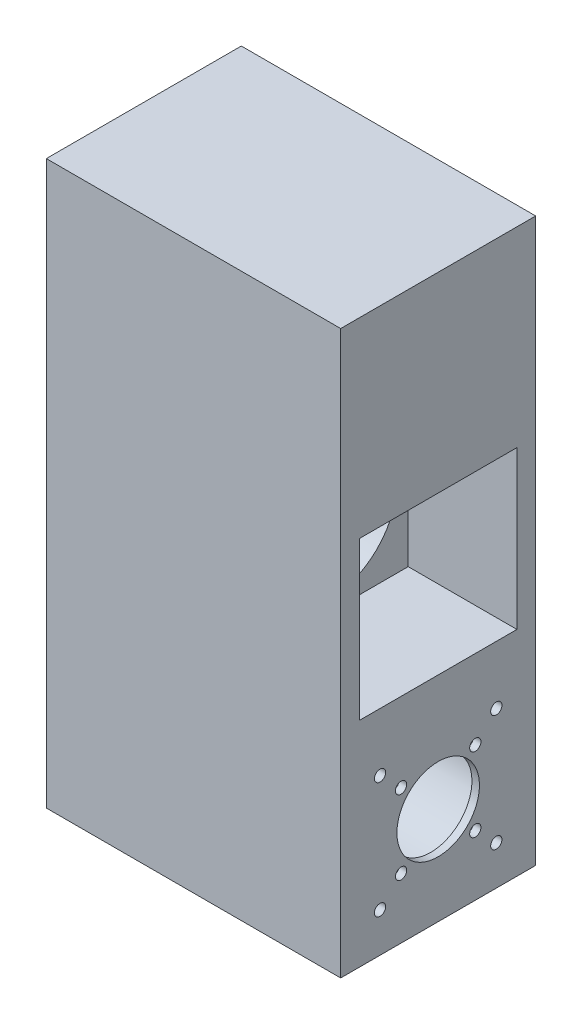
SolidWorks part; units mm, degrees
ref_plane "前视基准面" through (0, 0, 0) normal (0, 0, 1) x (1, 0, 0)
ref_plane "上视基准面" through (0, 0, 0) normal (0, 1, 0) x (1, 0, 0)
ref_plane "右视基准面" through (0, 0, 0) normal (1, 0, 0) x (0, 0, -1)
sketch "草图1" plane through (0, 0, 0) normal (0, 1, 0) x (1, 0, 0)
  line L1 (-39.25, 26) -> (39.25, 26)
  line L2 (-39.25, 26) -> (-39.25, -26)
  line L3 (-39.25, -26) -> (39.25, -26)
  line L4 (39.25, 26) -> (39.25, -26)
  line L5 (-39.25, 26) -> (39.25, -26) construction
  line L6 (-39.25, -26) -> (39.25, 26) construction
  point P0 (0, 0)
  dimension "D1" = 78.5
  dimension "D2" = 52
extrude "凸台-拉伸1" add sketch "草图1" along normal blind 150
sketch "草图2" plane through (-39.25, 0, 0) normal (-1, 0, 0) x (0, 0, 1)
  line L0 (-26, 0) -> (26, 0)
  line L1 (-26, 0) -> (-26, 52)
  line L2 (26, 0) -> (26, 52)
  line L3 (-26, 52) -> (26, 52)
  line L5 (-26, 26) -> (26, 26) construction
  line L6 (0, 52) -> (0, 0) construction
  line L7 (-21, 47) -> (21, 47)
  line L8 (-21, 47) -> (-21, 5)
  line L9 (-21, 5) -> (21, 5)
  line L10 (21, 47) -> (21, 5)
  line L11 (-21, 47) -> (21, 5) construction
  line L12 (-21, 5) -> (21, 47) construction
  point P0 (0, 26)
  dimension "D1" = 52
  dimension "D2" = 42
extrude "切除-拉伸1" cut sketch "草图2" against normal blind 38 contours L8 L7 L10 L9
sketch "草图3" plane through (-1.25, 0, 0) normal (-1, 0, 0) x (0, 0, 1)
  line L0 (-21, 47) -> (21, 5) construction
  line L1 (21, 47) -> (-21, 5) construction
  line L4 (-26, 0) -> (26, 0)
  line L5 (26, 0) -> (26, 52)
  line L6 (26, 52) -> (-26, 52)
  line L7 (-26, 52) -> (-26, 0)
  line L8 (-26, 0) -> (26, 0)
  line L9 (26, 0) -> (26, 52)
  line L10 (26, 52) -> (-26, 52)
  line L11 (-26, 52) -> (-26, 0)
  line L12 (21, 47) -> (-21, 47)
  line L13 (-21, 47) -> (-21, 5)
  line L14 (-21, 5) -> (21, 5)
  line L15 (21, 5) -> (21, 47)
  line L16 (21, 47) -> (-21, 47)
  line L17 (-21, 47) -> (-21, 5)
  line L18 (-21, 5) -> (21, 5)
  line L19 (21, 5) -> (21, 47)
  circle A0 centre (0, 26) radius 18
  dimension "D3" = 36
  dimension "D1" = 0
  dimension "D2" = 0
extrude "切除-拉伸2" cut sketch "草图3" against normal blind 38.5 contours A0
sketch "草图4" plane through (37.25, 0, 0) normal (-1, 0, 0) x (0, 0, 1)
  line L4 (-26, 0) -> (26, 0)
  line L5 (26, 0) -> (26, 52)
  line L6 (26, 52) -> (-26, 52)
  line L7 (-26, 52) -> (-26, 0)
  line L8 (-26, 0) -> (26, 0)
  line L9 (26, 0) -> (26, 52)
  line L10 (26, 52) -> (-26, 52)
  line L11 (-26, 52) -> (-26, 0)
  line L12 (21, 47) -> (-21, 47)
  line L13 (-21, 47) -> (-21, 5)
  line L14 (-21, 5) -> (21, 5)
  line L15 (21, 5) -> (21, 47)
  line L16 (21, 47) -> (-21, 47)
  line L17 (-21, 47) -> (-21, 5)
  line L18 (-21, 5) -> (21, 5)
  line L19 (21, 5) -> (21, 47)
  circle A0 centre (0, 26) radius 11
  circle A1 centre (0, 26) radius 18 construction
  dimension "D3" = 22
  dimension "D1" = 0
  dimension "D2" = 0
extrude "切除-拉伸3" cut sketch "草图4" against normal up to next contours A0
sketch "草图5" plane through (39.25, 0, 0) normal (1, 0, 0) x (0, 0, -1)
  line L0 (-21, 47) -> (21, 5) construction
  line L1 (21, 47) -> (-21, 5) construction
  line L4 (21, 47) -> (-21, 47)
  line L5 (21, 5) -> (21, 47)
  line L6 (-21, 5) -> (21, 5)
  line L7 (-21, 47) -> (-21, 5)
  line L8 (21, 47) -> (-21, 47)
  line L9 (21, 5) -> (21, 47)
  line L10 (-21, 5) -> (21, 5)
  line L11 (-21, 47) -> (-21, 5)
  line L12 (-26, 0) -> (26, 0)
  line L13 (-26, 52) -> (-26, 0)
  line L14 (26, 52) -> (-26, 52)
  line L15 (26, 0) -> (26, 52)
  line L16 (-26, 0) -> (26, 0)
  line L17 (-26, 52) -> (-26, 0)
  line L18 (26, 52) -> (-26, 52)
  line L19 (26, 0) -> (26, 52)
  circle A0 centre (0, 26) radius 14
  circle A1 centre (0, 26) radius 11
  circle A2 centre (0, 26) radius 11
  circle A3 centre (-9.8995, 35.8995) radius 1.5
  circle A7 centre (9.8995, 35.8995) radius 1.5
  circle A8 centre (9.8995, 16.1005) radius 1.5
  circle A9 centre (-9.8995, 16.1005) radius 1.5
  dimension "D4" = 28
  dimension "D5" = 3
  dimension "D1" = 0
  dimension "D2" = 0
  dimension "D3" = 0
extrude "切除-拉伸4" cut sketch "草图5" against normal up to next contours A3 | A7 | A9 | A8
sketch "草图8" plane through (39.25, 0, 0) normal (1, 0, 0) x (0, 0, -1)
  line L0 (-21, 47) -> (21, 5) construction
  line L1 (21, 47) -> (-21, 5) construction
  line L4 (21, 47) -> (-21, 47)
  line L5 (21, 5) -> (21, 47)
  line L6 (-21, 5) -> (21, 5)
  line L7 (-21, 47) -> (-21, 5)
  line L8 (21, 47) -> (-21, 47)
  line L9 (21, 5) -> (21, 47)
  line L10 (-21, 5) -> (21, 5)
  line L11 (-21, 47) -> (-21, 5)
  line L12 (-26, 0) -> (26, 0)
  line L13 (-26, 52) -> (-26, 0)
  line L14 (26, 52) -> (-26, 52)
  line L15 (26, 0) -> (26, 52)
  line L16 (-26, 0) -> (26, 0)
  line L17 (-26, 52) -> (-26, 0)
  line L18 (26, 52) -> (-26, 52)
  line L19 (26, 0) -> (26, 52)
  circle A0 centre (-15.5, 41.5) radius 1.5
  circle A1 centre (0, 26) radius 11
  circle A2 centre (0, 26) radius 11
  circle A3 centre (15.5, 41.5) radius 1.5
  circle A4 centre (-15.5, 10.5) radius 1.5
  circle A5 centre (15.5, 10.5) radius 1.5
  point P19 (0, 0)
  point P20 (0, 0)
  point P21 (0, 0)
  point P22 (0, 0)
  dimension "D4" = 3
  dimension "D5" = 31
  dimension "D1" = 0
  dimension "D2" = 0
  dimension "D3" = 0
extrude "切除-拉伸5" cut sketch "草图8" against normal up to next contours A0 | A3 | A4 | A5
sketch "草图15" plane through (-39.25, 0, 0) normal (-1, 0, 0) x (0, 0, 1)
  line L0 (-26, 150) -> (26, 52) construction
  line L1 (26, 52) -> (-26, 52)
  line L2 (26, 52) -> (26, 150)
  line L3 (26, 150) -> (-26, 150)
  line L4 (-26, 0) -> (26, 0)
  line L5 (26, 0) -> (26, 52)
  line L6 (26, 52) -> (-26, 52)
  line L7 (-26, 52) -> (-26, 0)
  line L8 (-26, 0) -> (26, 0)
  line L9 (26, 0) -> (26, 52)
  line L10 (26, 52) -> (-26, 52)
  line L11 (-26, 52) -> (-26, 0)
  line L12 (21, 47) -> (-21, 47)
  line L13 (-21, 47) -> (-21, 5)
  line L14 (-21, 5) -> (21, 5)
  line L15 (21, 5) -> (21, 47)
  line L16 (21, 47) -> (-21, 47)
  line L17 (-21, 47) -> (-21, 5)
  line L18 (-21, 5) -> (21, 5)
  line L19 (21, 5) -> (21, 47)
  line L20 (-26, 52) -> (-26, 150)
  line L21 (26, 150) -> (-26, 52) construction
  line L23 (-21, 145) -> (21, 145)
  line L24 (-21, 145) -> (-21, 57)
  line L25 (-21, 57) -> (21, 57)
  line L26 (21, 145) -> (21, 57)
  line L27 (-21, 145) -> (21, 57) construction
  line L28 (-21, 57) -> (21, 145) construction
  point P10 (0, 101)
  dimension "D3" = 5
  dimension "D4" = 5
  dimension "D1" = 0
  dimension "D2" = 0
extrude "切除-拉伸13" cut sketch "草图15" against normal blind 20 contours L26 L23 L24 L25
sketch "草图16" plane through (-19.25, 0, 0) normal (-1, 0, 0) x (0, 0, 1)
  line L0 (21, 57) -> (-21, 57)
  line L1 (21, 57) -> (21, 99)
  line L2 (-21, 57) -> (-21, 99)
  line L3 (21, 99) -> (-21, 99)
  line L4 (-21, 99) -> (21, 57) construction
  line L5 (21, 99) -> (-21, 57) construction
  circle A0 centre (0, 78) radius 11
  dimension "D2" = 22
  dimension "D1" = 42
extrude "切除-拉伸14" cut sketch "草图16" against normal blind 2 contours A0
sketch "草图17" plane through (-17.25, 0, 0) normal (-1, 0, 0) x (0, 0, 1)
  line L4 (-21, 57) -> (21, 57)
  line L5 (-21, 99) -> (-21, 57)
  line L6 (21, 99) -> (-21, 99)
  line L7 (21, 57) -> (21, 99)
  line L8 (-21, 57) -> (21, 57)
  line L9 (-21, 99) -> (-21, 57)
  line L10 (21, 99) -> (-21, 99)
  line L11 (21, 57) -> (21, 99)
  circle A0 centre (0, 78) radius 18
  circle A1 centre (0, 78) radius 11
  circle A2 centre (0, 78) radius 11
  dimension "D3" = 36
  dimension "D1" = 0
  dimension "D2" = 0
extrude "切除-拉伸15" cut sketch "草图17" against normal blind 27.5 contours A0
sketch "草图18" plane through (10.25, 0, 0) normal (-1, 0, 0) x (0, 0, 1)
  line L1 (-21, 99) -> (21, 99)
  line L2 (-21, 99) -> (-21, 57)
  line L3 (-21, 57) -> (21, 57)
  line L4 (-21, 57) -> (21, 57)
  line L5 (-21, 99) -> (-21, 57)
  line L6 (21, 99) -> (-21, 99)
  line L7 (21, 57) -> (21, 99)
  line L8 (-21, 57) -> (21, 57)
  line L9 (-21, 99) -> (-21, 57)
  line L10 (21, 99) -> (-21, 99)
  line L11 (21, 57) -> (21, 99)
  line L12 (21, 99) -> (21, 57)
  circle A1 centre (0, 78) radius 11
  circle A2 centre (0, 78) radius 11
  circle M6 centre (0, 78) radius 18
  dimension "D1" = 0
  dimension "D2" = 0
extrude "切除-拉伸16" cut sketch "草图18" against normal up to surface (29 mm away) contours L3 L11 L1 L2 M6 | A2 | A2 M6 up to face at (39.25, 41.5, -17)
sketch "草图19" plane through (-19.25, 0, 0) normal (-1, 0, 0) x (0, 0, 1)
  line L0 (-21, 99) -> (21, 57) construction
  line L1 (21, 99) -> (-21, 57) construction
  line L4 (-21, 57) -> (21, 57)
  line L5 (-21, 99) -> (-21, 57)
  line L6 (21, 99) -> (-21, 99)
  line L7 (21, 57) -> (21, 99)
  line L8 (-21, 57) -> (21, 57)
  line L9 (-21, 99) -> (-21, 57)
  line L10 (21, 99) -> (-21, 99)
  line L11 (21, 57) -> (21, 99)
  circle A0 centre (0, 78) radius 14
  circle A1 centre (0, 78) radius 11
  circle A2 centre (0, 78) radius 11
  circle A3 centre (-9.8995, 87.8995) radius 1.5
  circle A4 centre (9.8995, 87.8995) radius 1.5
  circle A6 centre (9.8995, 68.1005) radius 1.5
  circle A7 centre (-9.8995, 68.1005) radius 1.5
  point P16 (0, 0)
  point P17 (0, 0)
  dimension "D3" = 28
  dimension "D4" = 3
  dimension "D1" = 0
  dimension "D2" = 0
extrude "切除-拉伸17" cut sketch "草图19" against normal up to next contours A3 | A4 | A6 | A7
